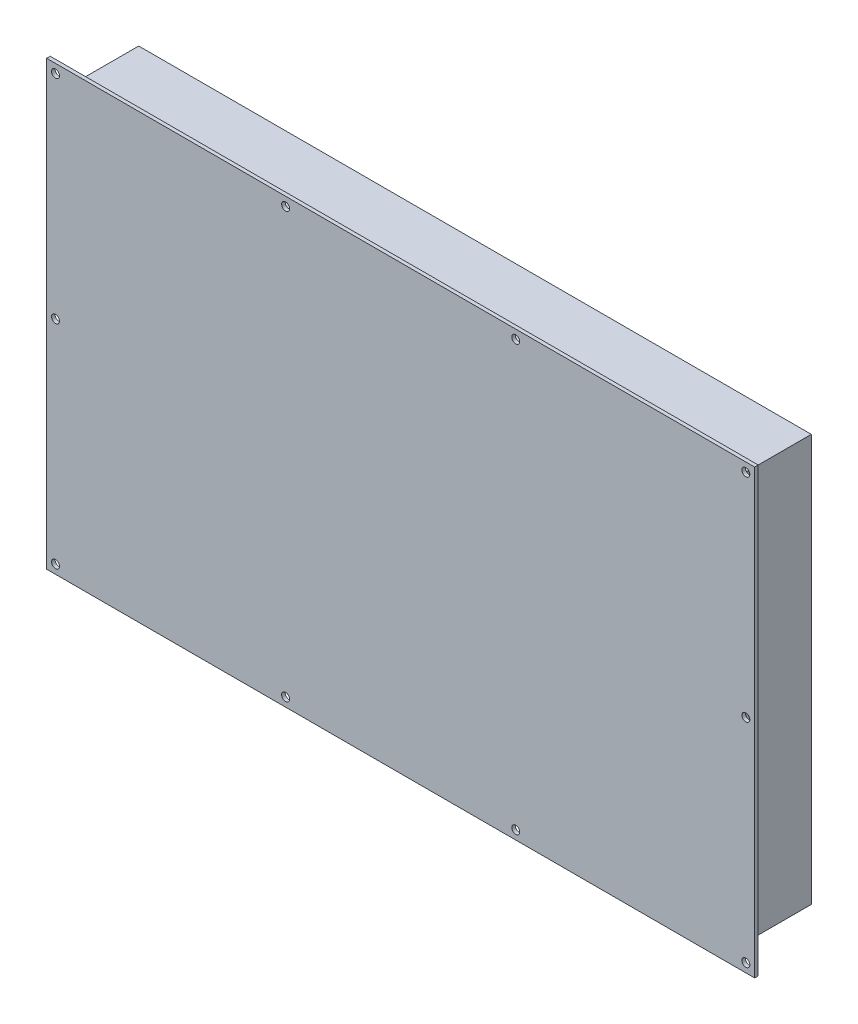
SolidWorks part; units mm, degrees
ref_plane "Ön Düzlem" through (0, 0, 0) normal (0, 0, 1) x (1, 0, 0)
ref_plane "Üst Düzlem" through (0, 0, 0) normal (0, 1, 0) x (1, 0, 0)
ref_plane "Sağ Düzlem" through (0, 0, 0) normal (1, 0, 0) x (0, 0, -1)
sketch "Çizim1" plane through (0, 0, 0) normal (0, 0, 1) x (1, 0, 0)
  line L1 (-200, -125) -> (200, -125)
  line L2 (-200, -125) -> (-200, 125)
  line L3 (-200, 125) -> (200, 125)
  line L4 (200, -125) -> (200, 125)
  line L5 (-200, -125) -> (200, 125) construction
  line L6 (-200, 125) -> (200, -125) construction
  point P0 (0, 0)
  dimension "D1" = 400
  dimension "D2" = 250
extrude "Yükseklik-Ekstrüzyon1" add sketch "Çizim1" along normal blind 2
sketch "Çizim3" plane through (0, 0, 2) normal (0, 0, 1) x (1, 0, 0)
  line L2 (0, 0) -> (109.1985, 0) construction
  circle A0 centre (-195, 120) radius 2.25
  circle A1 centre (-65, 120) radius 2.25
  circle A2 centre (65, 120) radius 2.25
  circle A3 centre (195, 120) radius 2.25
  circle A4 centre (-65, -120) radius 2.25
  circle A5 centre (65, -120) radius 2.25
  circle A6 centre (195, -120) radius 2.25
  circle A7 centre (-195, -120) radius 2.25
  circle A8 centre (-195, 0) radius 2.25
  circle A9 centre (195, 0) radius 2.25
  dimension "D1" = 2
  dimension "D3" = 4.5
  dimension "D2" = 120
  dimension "D6" = 120
  dimension "D4" = 4
  dimension "D5" = 2
extrude "Kes-Ekstrüzyon1" cut sketch "Çizim3" against normal up to next
sketch "Çizim4" plane through (0, 0, 0) normal (0, 0, -1) x (-1, 0, 0)
  line L1 (-190, -115) -> (190, -115)
  line L2 (-190, -115) -> (-190, 115)
  line L3 (-190, 115) -> (190, 115)
  line L4 (190, -115) -> (190, 115)
  line L5 (-190, -115) -> (190, 115) construction
  line L6 (-190, 115) -> (190, -115) construction
  point P0 (0, 0)
  dimension "D1" = 230
  dimension "D2" = 380
extrude "Yükseklik-Ekstrüzyon2" add sketch "Çizim4" along normal blind 40
